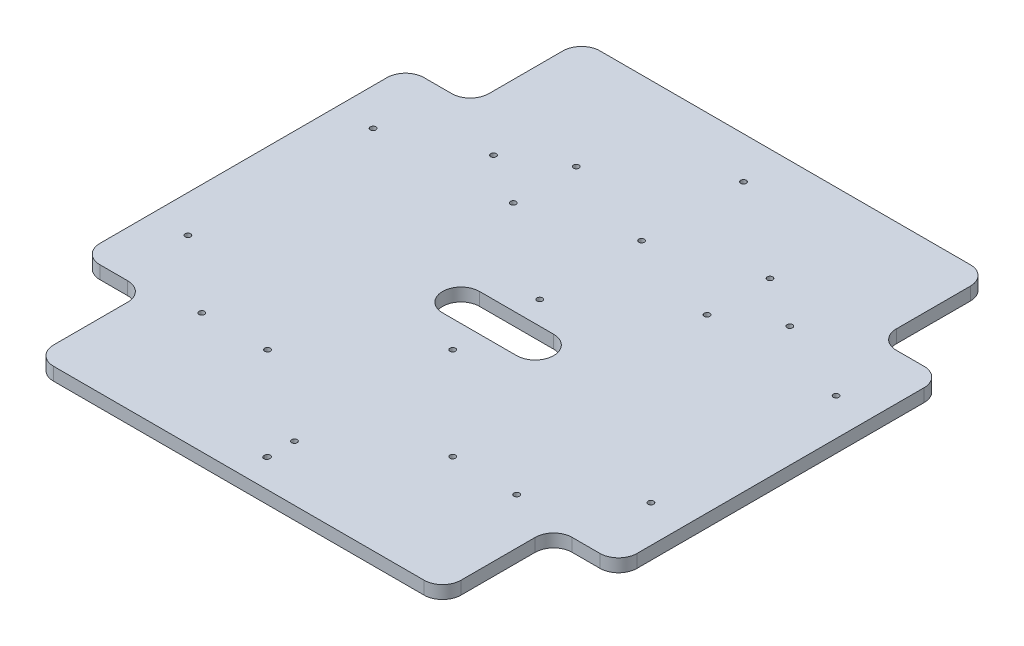
SolidWorks part; units mm, degrees
ref_plane "前视基准面" through (0, 0, 0) normal (0, 0, 1) x (1, 0, 0)
ref_plane "上视基准面" through (0, 0, 0) normal (0, 1, 0) x (1, 0, 0)
ref_plane "右视基准面" through (0, 0, 0) normal (1, 0, 0) x (0, 0, -1)
sketch "草图1" plane through (0, 0, 0) normal (0, 1, 0) x (1, 0, 0)
  line L1 (-150, 150) -> (150, 150)
  line L2 (-150, 150) -> (-150, -150)
  line L3 (-150, -150) -> (150, -150)
  line L4 (150, 150) -> (150, -150)
  line L5 (-150, 150) -> (150, -150) construction
  line L6 (-150, -150) -> (150, 150) construction
  point P0 (0, 0)
  dimension "D1" = 300
  dimension "D2" = 300
extrude "凸台-拉伸1" add sketch "草图1" along normal blind 7
sketch "草图2" plane through (0, 7, 0) normal (0, 1, 0) x (1, 0, 0)
  line L1 (-150, -150) -> (90, -150)
  line L2 (-150, -150) -> (-150, -147.5)
  line L3 (-150, -147.5) -> (90, -147.5)
  line L4 (90, -150) -> (90, -147.5)
extrude "切除-拉伸1" cut sketch "草图2" against normal blind 50
sketch "草图3" plane through (0, 7, 0) normal (0, 1, 0) x (1, 0, 0)
  line L0 (90, -150) -> (90, -147.5)
  line L1 (90, -147.5) -> (150, -147.5)
  line L2 (150, -150) -> (150, 150) construction
  line L3 (150, -147.5) -> (150, -150)
  line L4 (150, -150) -> (90, -150)
extrude "切除-拉伸2" cut sketch "草图3" against normal blind 50
sketch "草图4" plane through (0, 7, 0) normal (0, 1, 0) x (1, 0, 0)
  line L0 (-60.2347, 147.5) -> (-150, 147.5)
  line L1 (-90, 147.5) -> (90, 147.5) construction
  line L2 (-150, 150) -> (-150, -147.5) construction
  line L3 (-150, 147.5) -> (-150, 150)
  line L4 (-150, 150) -> (150, 150)
  line L5 (150, 150) -> (150, 148.75)
  line L6 (150, -147.5) -> (150, 150) construction
  line L7 (-60.2347, 147.5) -> (150, 147.5)
  line L8 (150, 147.5) -> (150, 148.75)
extrude "切除-拉伸3" cut sketch "草图4" against normal blind 50
sketch "草图5" plane through (0, 7, 0) normal (0, 1, 0) x (1, 0, 0)
  line L0 (-145, -36.2732) -> (-145, -168.0775)
  line L1 (-145, -60) -> (-145, 60) construction
  line L2 (-145, -168.0775) -> (-167.0851, -168.0775)
  line L3 (-167.0851, -168.0775) -> (-167.0851, 166.9666)
  line L4 (-167.0851, 166.9666) -> (-145, 166.9666)
  line L5 (-145, 166.9666) -> (-145, -36.2732)
extrude "切除-拉伸4" cut sketch "草图5" against normal blind 50
sketch "草图6" plane through (0, 7, 0) normal (0, 1, 0) x (1, 0, 0)
  line L0 (150, -147.5) -> (150, 173.3726)
  line L1 (145, -12.7062) -> (145, 173.3726)
  line L2 (145, 60) -> (145, -60) construction
  line L3 (145, 173.3726) -> (150, 173.3726)
  line L4 (145, -12.7062) -> (145, -195.2322)
  line L5 (145, -195.2322) -> (157.0678, -195.2322)
  line L6 (157.0678, -195.2322) -> (150, -147.5)
extrude "切除-拉伸5" cut sketch "草图6" against normal blind 50
sketch "草图7" plane through (0, 0, 0) normal (0, -1, 0) x (1, 0, 0)
  line L1 (-145, 147.5) -> (-110, 147.5)
  line L2 (-145, 147.5) -> (-145, 87.5)
  line L3 (-145, 87.5) -> (-110, 87.5)
  line L4 (-110, 147.5) -> (-110, 87.5)
  line L5 (-145, -147.5) -> (-110, -147.5)
  line L6 (-145, -147.5) -> (-145, -87.5)
  line L7 (-145, -87.5) -> (-110, -87.5)
  line L8 (-110, -147.5) -> (-110, -87.5)
  line L9 (145, 147.5) -> (110, 147.5)
  line L10 (145, 147.5) -> (145, 87.5)
  line L11 (145, 87.5) -> (110, 87.5)
  line L12 (110, 147.5) -> (110, 87.5)
  line L13 (145, -147.5) -> (110, -147.5)
  line L14 (145, -147.5) -> (145, -87.5)
  line L15 (145, -87.5) -> (110, -87.5)
  line L16 (110, -147.5) -> (110, -87.5)
  dimension "D1" = 60
  dimension "D2" = 35
  dimension "D3" = 60
  dimension "D4" = 35
  dimension "D5" = 60
  dimension "D6" = 35
  dimension "D7" = 60
  dimension "D8" = 35
extrude "切除-拉伸6" cut sketch "草图7" against normal blind 50
sketch "草图8" plane through (0, 7, 0) normal (0, 1, 0) x (1, 0, 0)
  line L0 (-237.778, 0) -> (269.9588, 0) construction
  line L1 (0, -328.5201) -> (0, 218.1617) construction
  line L2 (-125, 345.4675) -> (-125, -473.6983) construction
  line L3 (125, 345.4675) -> (125, -431.7658) construction
  line L4 (145, 60) -> (145, -60) construction
  line L5 (-145, -60) -> (-145, 60) construction
  line L6 (-135, 70) -> (-110, 70) construction
  line L7 (-110, -70) -> (-135, -70) construction
  line L8 (135, -70) -> (110, -70) construction
  line L9 (110, 70) -> (135, 70) construction
  line L10 (-100, 80) -> (100, 80) construction
  line L11 (-100, 80) -> (-100, 137.5) construction
  line L12 (100, 137.5) -> (100, 80) construction
  line L13 (90, -147.5) -> (-90, -147.5) construction
  circle A0 centre (-125, 50) radius 1.5
  circle A1 centre (-125, -50) radius 1.5
  circle A2 centre (125, -50) radius 1.5
  circle A3 centre (125, 50) radius 1.5
  arc A4 (-110, 70) -> (-100, 80) centre (-110, 80) ccw construction
  circle A5 centre (-80, 70) radius 1.5
  circle A6 centre (80, 70) radius 1.5
  circle A7 centre (0, 70) radius 1.5
  circle A8 centre (0, -132.5) radius 1.5
  circle A9 centre (-85, -82.5) radius 1.5
  circle A10 centre (85, -82.5) radius 1.5
  dimension "D3" = 3
  dimension "D4" = 3
  dimension "D5" = 3
  dimension "D6" = 3
  dimension "D7" = 20
  dimension "D8" = 20
  dimension "D10" = 20
  dimension "D11" = 3
  dimension "D12" = 3
  dimension "D13" = 10
  dimension "D14" = 20
  dimension "D15" = 10
  dimension "D16" = 20
  dimension "D17" = 3
  dimension "D18" = 3
  dimension "D19" = 15
  dimension "D20" = 3
  dimension "D21" = 3
  dimension "D24" = 65
  dimension "D25" = 65
  dimension "D1" = 20
  dimension "D2" = 20
  dimension "D9" = 20
  dimension "D22" = 85
  dimension "D23" = 85
  dimension "D26" = 10
extrude "切除-拉伸7" cut sketch "草图8" against normal blind 500
fillet "圆角1" radius 10 2 edges at (110, 3.5, 147.5) (-110, 3.5, 147.5)
fillet "圆角2" radius 10 2 edges at (110, 3.5, 87.5) (-110, 3.5, 87.5)
fillet "圆角3" radius 10 2 edges at (-145, 3.5, 87.5) (145, 3.5, 87.5)
fillet "圆角4" radius 10 2 edges at (145, 3.5, -87.5) (-145, 3.5, -87.5)
fillet "圆角5" radius 10 2 edges at (-110, 3.5, -87.5) (110, 3.5, -87.5)
fillet "圆角6" radius 10 2 edges at (110, 3.5, -147.5) (-110, 3.5, -147.5)
sketch "草图9" plane through (0, 7, 0) normal (0, 1, 0) x (1, 0, 0)
  circle A0 centre (0, 70) radius 55 construction
  circle A1 centre (0, 125) radius 1.5
  dimension "D1" = 110
  dimension "D2" = 3
extrude "切除-拉伸8" cut sketch "草图9" against normal blind 50
pattern_circular "阵列(圆周)1" count 10 over 360 about axis through (0, 0, -70) along (0, 1, 0) of "切除-拉伸8"
sketch "草图11" plane through (0, 7, 0) normal (0, 1, 0) x (1, 0, 0)
  circle A0 centre (-32.3282, 114.4959) radius 3.3008
  circle A1 centre (32.3282, 114.4959) radius 5.7375
  circle A2 centre (-32.3282, 25.5041) radius 4.8507
  circle A3 centre (32.3282, 25.5041) radius 5.0431
extrude "凸台-拉伸3" add sketch "草图11" against normal up to surface (7 mm away) up to face at (32.3282, 0, -112.9959)
sketch "草图12" plane through (0, 0, 0) normal (0, -1, 0) x (1, 0, 0)
  line L0 (-311.1688, 7.5) -> (617.603, 7.5) construction
  line L1 (100, 147.5) -> (-100, 147.5) construction
  line L2 (0, 211.6262) -> (0, -240.425) construction
  line L3 (-20, 7.5) -> (20, 7.5) construction
  line L4 (-20, 17.5) -> (20, 17.5)
  line L5 (-20, -2.5) -> (20, -2.5)
  arc A0 (-20, 17.5) -> (-20, -2.5) centre (-20, 7.5) ccw
  arc A1 (20, -2.5) -> (20, 17.5) centre (20, 7.5) ccw
  point P2 (0, 7.5)
  point P9 (0, 7.5)
  dimension "D1" = 140
  dimension "D2" = 40
  dimension "D3" = 20
extrude "切除-拉伸9" cut sketch "草图12" against normal blind 50
sketch "草图13" plane through (0, 0, 0) normal (0, -1, 0) x (1, 0, 0)
  line L0 (0, 275.6549) -> (0, -308.5757) construction
sketch "草图14" plane through (0, 0, 0) normal (0, -1, 0) x (1, 0, 0)
  line L0 (0, 275.6549) -> (0, -308.5757) construction
  line L1 (-75.3095, 82) -> (99.4481, 82) construction
  circle A0 centre (0, 115) radius 25 construction
  circle A1 centre (0, 82) radius 58 construction
  circle A2 centre (0, 132) radius 1.5
  circle A3 centre (-50, 82) radius 1.5
  circle A4 centre (50, 82) radius 1.5
  circle A5 centre (0, 32) radius 1.5
  point P0 (0, 82)
  point P1 (0, 140)
  dimension "D2" = 3
  dimension "D3" = 3
  dimension "D4" = 3
  dimension "D5" = 3
  dimension "D6" = 50
  dimension "D7" = 50
  dimension "D8" = 50
  dimension "D9" = 50
  dimension "D1" = 58
extrude "切除-拉伸10" cut sketch "草图14" against normal blind 50
sketch "草图15" plane through (0, 0, 0) normal (0, -1, 0) x (1, 0, 0)
  line L0 (0, 275.6549) -> (0, -308.5757) construction
  line L1 (100, 147.5) -> (-100, 147.5) construction
  circle A0 centre (0, 117.5) radius 1.5
  dimension "D1" = 3
  dimension "D2" = 30
extrude "切除-拉伸11" cut sketch "草图15" against normal blind 50
